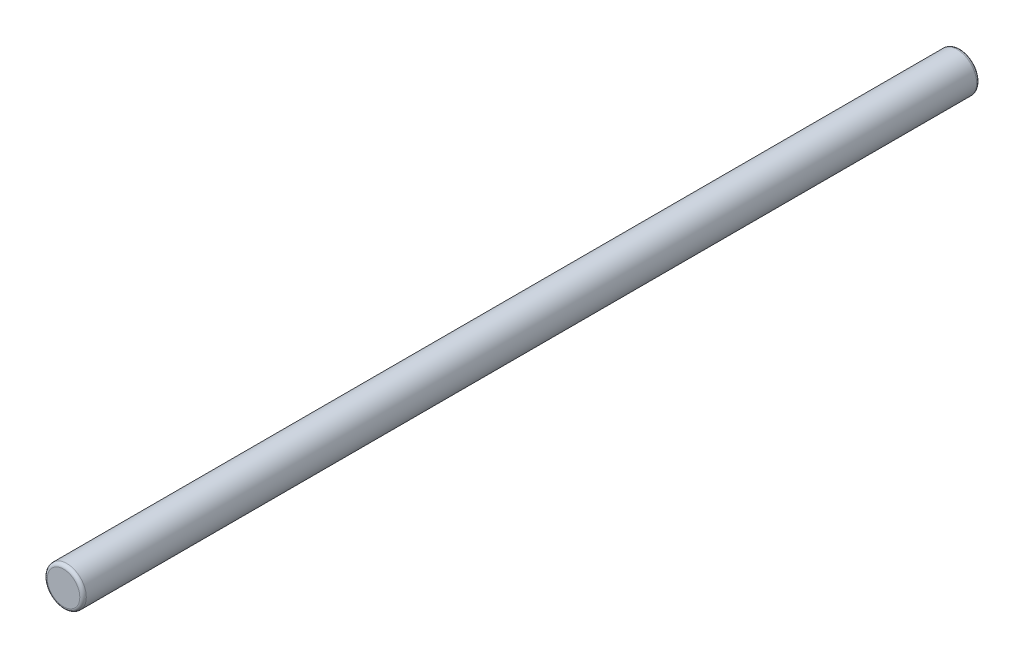
SolidWorks part; units mm, degrees
ref_plane "Plano frontal" through (0, 0, 0) normal (0, 0, 1) x (1, 0, 0)
ref_plane "Plano superior" through (0, 0, 0) normal (0, 1, 0) x (1, 0, 0)
ref_plane "Plano direito" through (0, 0, 0) normal (1, 0, 0) x (0, 0, -1)
sketch "Esboço1" plane through (0, 0, 0) normal (0, 0, 1) x (1, 0, 0)
  circle A0 centre (0, 0) radius 3
  dimension "D1" = 6
extrude "Ressalto-extrusão1" add sketch "Esboço1" along normal blind 138
fillet "Filete1" radius 0.5 2 edges at (3, 0, 0) (3, 0, 138)
